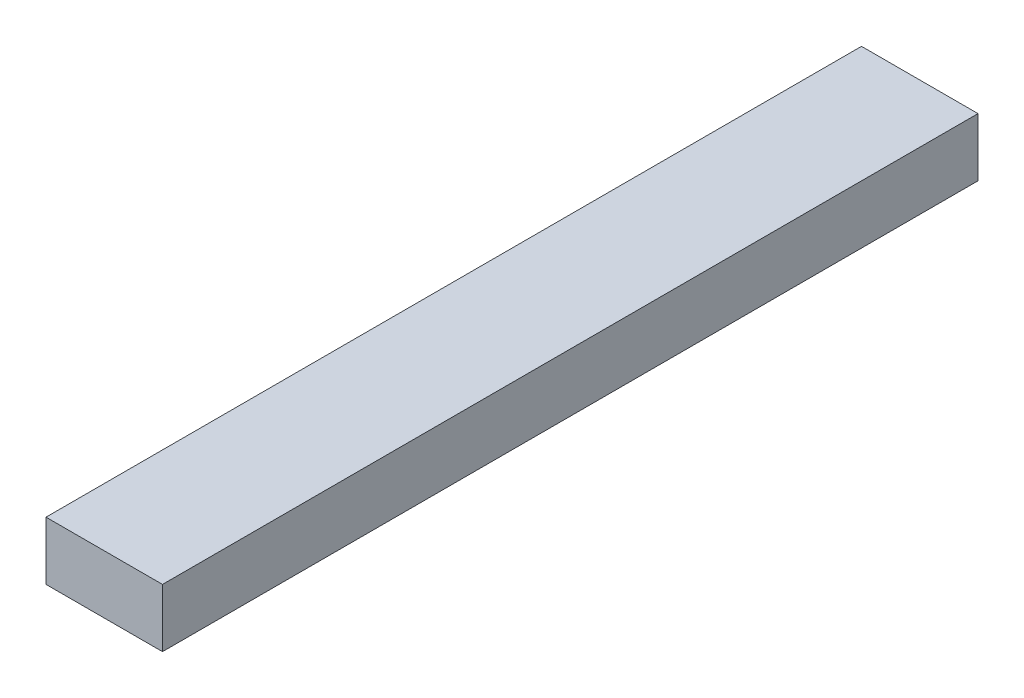
SolidWorks part; units mm, degrees
ref_plane "Front Plane" through (0, 0, 0) normal (0, 0, 1) x (1, 0, 0)
ref_plane "Top Plane" through (0, 0, 0) normal (0, 1, 0) x (1, 0, 0)
ref_plane "Right Plane" through (0, 0, 0) normal (1, 0, 0) x (0, 0, -1)
sketch "Sketch1" plane through (0, 0, 0) normal (0, 0, 1) x (1, 0, 0)
  line L1 (-50.8, -25.4) -> (50.8, -25.4)
  line L2 (-50.8, -25.4) -> (-50.8, 25.4)
  line L3 (-50.8, 25.4) -> (50.8, 25.4)
  line L4 (50.8, -25.4) -> (50.8, 25.4)
  line L5 (-50.8, -25.4) -> (50.8, 25.4) construction
  line L6 (-50.8, 25.4) -> (50.8, -25.4) construction
  point P0 (0, 0)
  dimension "D1" = 50.8
  dimension "D2" = 101.6
extrude "Boss-Extrude1" add sketch "Sketch1" along normal blind 914.4
sketch "Sketch2" plane through (0, 0, 0) normal (0, 0, -1) x (-1, 0, 0)
  line L4 (-50.8, 25.4) -> (-50.8, -25.4)
  line L5 (-50.8, -25.4) -> (50.8, -25.4)
  line L6 (50.8, -25.4) -> (50.8, 25.4)
  line L7 (50.8, 25.4) -> (-50.8, 25.4)
  line L8 (-50.8, 25.4) -> (-50.8, -25.4)
  line L9 (-50.8, -25.4) -> (50.8, -25.4)
  line L10 (50.8, -25.4) -> (50.8, 25.4)
  line L11 (50.8, 25.4) -> (-50.8, 25.4)
  dimension "D1" = 0
extrude "Cut-Extrude1" cut sketch "Sketch2" against normal blind 101.6
sketch "Sketch3" plane through (0, 25.4, 0) normal (0, 1, 0) x (1, 0, 0)
  line L0 (-50.8, -914.4) -> (-50.8, -812.8)
  line L1 (-50.8, -914.4) -> (-50.8, -101.6) construction
  line L2 (-50.8, -812.8) -> (50.8, -812.8)
  line L3 (50.8, -914.4) -> (50.8, -101.6) construction
  line L4 (50.8, -812.8) -> (1168.4, -812.8) construction
  line L6 (50.8, -812.8) -> (50.8, -914.4)
  line L7 (-50.8, -914.4) -> (50.8, -914.4)
  point P10 (-50.8, -812.8)
extrude "Cut-Extrude2" cut sketch "Sketch3" against normal blind 50.8
